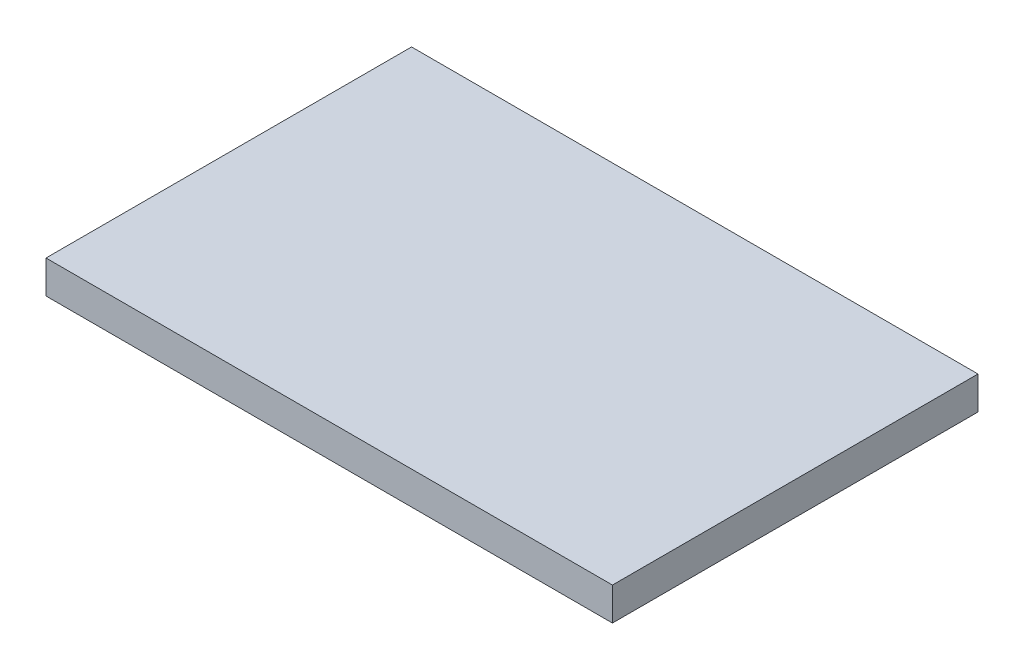
SolidWorks part; units mm, degrees
ref_plane "Front Plane" through (0, 0, 0) normal (0, 0, 1) x (1, 0, 0)
ref_plane "Top Plane" through (0, 0, 0) normal (0, 1, 0) x (1, 0, 0)
ref_plane "Right Plane" through (0, 0, 0) normal (1, 0, 0) x (0, 0, -1)
sketch "Sketch1" plane through (0, 0, 0) normal (0, 1, 0) x (1, 0, 0)
  line L1 (0, 0) -> (17.2, 0)
  line L2 (0, 0) -> (0, -11.1)
  line L3 (0, -11.1) -> (17.2, -11.1)
  line L4 (17.2, 0) -> (17.2, -11.1)
  dimension "D1" = 11.1
  dimension "D2" = 17.2
extrude "Boss-Extrude1" add sketch "Sketch1" along normal blind 1
